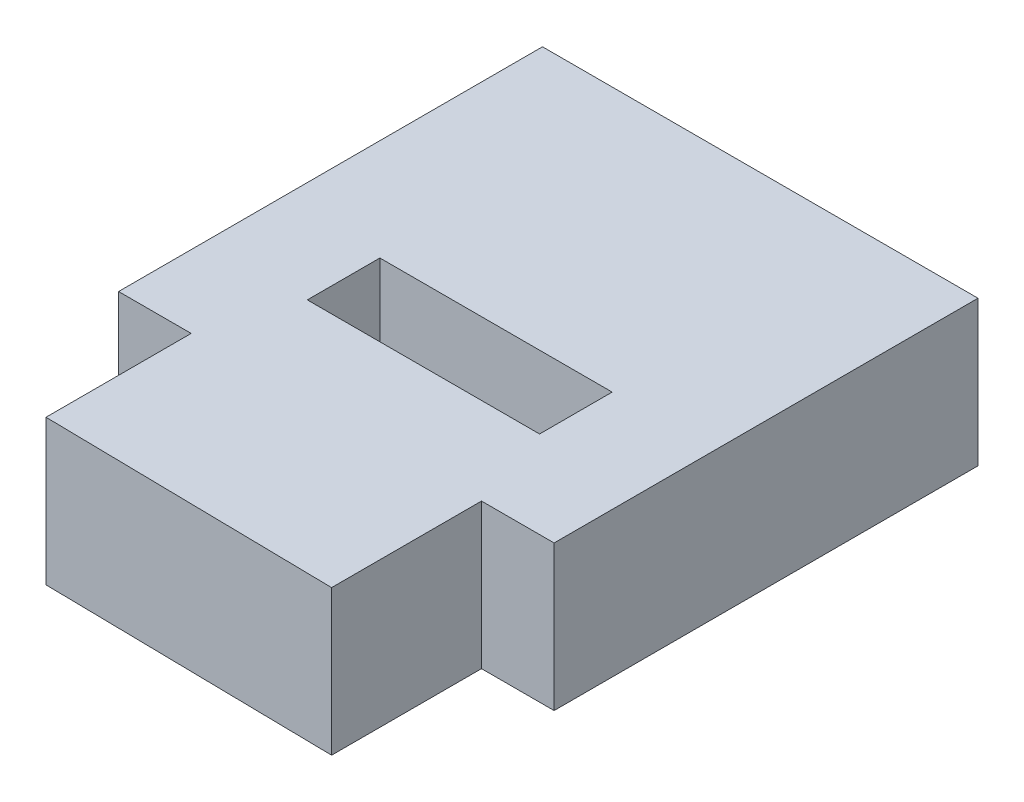
SolidWorks part; units mm, degrees
material "Maple"
ref_plane "Front Plane" through (0, 0, 0) normal (0, 0, 1) x (1, 0, 0)
ref_plane "Top Plane" through (0, 0, 0) normal (0, 1, 0) x (1, 0, 0)
ref_plane "Right Plane" through (0, 0, 0) normal (1, 0, 0) x (0, 0, -1)
sketch "Sketch1" plane through (0, 0, 0) normal (0, 1, 0) x (1, 0, 0)
  line L0 (-6.35, -15.621) -> (6.35, -9.271) construction
  line L1 (9.525, -9.271) -> (-9.525, -9.271) construction
  line L2 (9.525, -9.271) -> (9.525, 9.271) construction
  line L3 (9.525, 9.271) -> (-9.525, 9.271) construction
  line L4 (-9.525, -9.271) -> (-9.525, 9.271) construction
  line L5 (9.525, -9.271) -> (-9.525, 9.271) construction
  line L6 (9.525, 9.271) -> (-9.525, -9.271) construction
  line L7 (-6.35, -9.271) -> (6.35, -9.271) construction
  line L8 (-6.35, -9.271) -> (-6.35, -15.621) construction
  line L9 (-6.35, -15.621) -> (6.35, -15.621) construction
  line L10 (6.35, -9.271) -> (6.35, -15.621) construction
  line L11 (-9.525, 9.271) -> (9.525, 9.271)
  line L12 (9.525, 9.271) -> (9.525, -9.271)
  line L13 (9.525, -9.271) -> (6.35, -9.271)
  line L14 (6.35, -9.271) -> (6.35, -15.8285)
  line L15 (6.35, -15.8285) -> (-6.35, -15.621)
  line L16 (-6.35, -15.621) -> (-6.35, -9.271)
  line L17 (-6.35, -9.271) -> (-9.525, -9.271)
  line L18 (-9.525, -9.271) -> (-9.525, 9.271)
  line L19 (0, 9.271) -> (0, -9.271) construction
  line L21 (-5.08, -5.461) -> (5.08, -5.461)
  line L22 (-5.08, -5.461) -> (-5.08, -2.286)
  line L23 (-5.08, -2.286) -> (5.08, -2.286)
  line L24 (5.08, -5.461) -> (5.08, -2.286)
  line L25 (-5.08, -5.461) -> (5.08, -2.286) construction
  line L26 (-5.08, -2.286) -> (5.08, -5.461) construction
  point P0 (0, 0)
  point P10 (0, -12.446)
  point P11 (6.35, -12.446)
  point P15 (0, -3.8735)
  dimension "D1" = 18.542
  dimension "D2" = 19.05
  dimension "D3" = 6.35
  dimension "D4" = 12.7
  dimension "D5" = 3.175
  dimension "D6" = 10.16
  dimension "D7" = 3.81
extrude "Boss-Extrude1" add sketch "Sketch1" along normal blind 6.35
